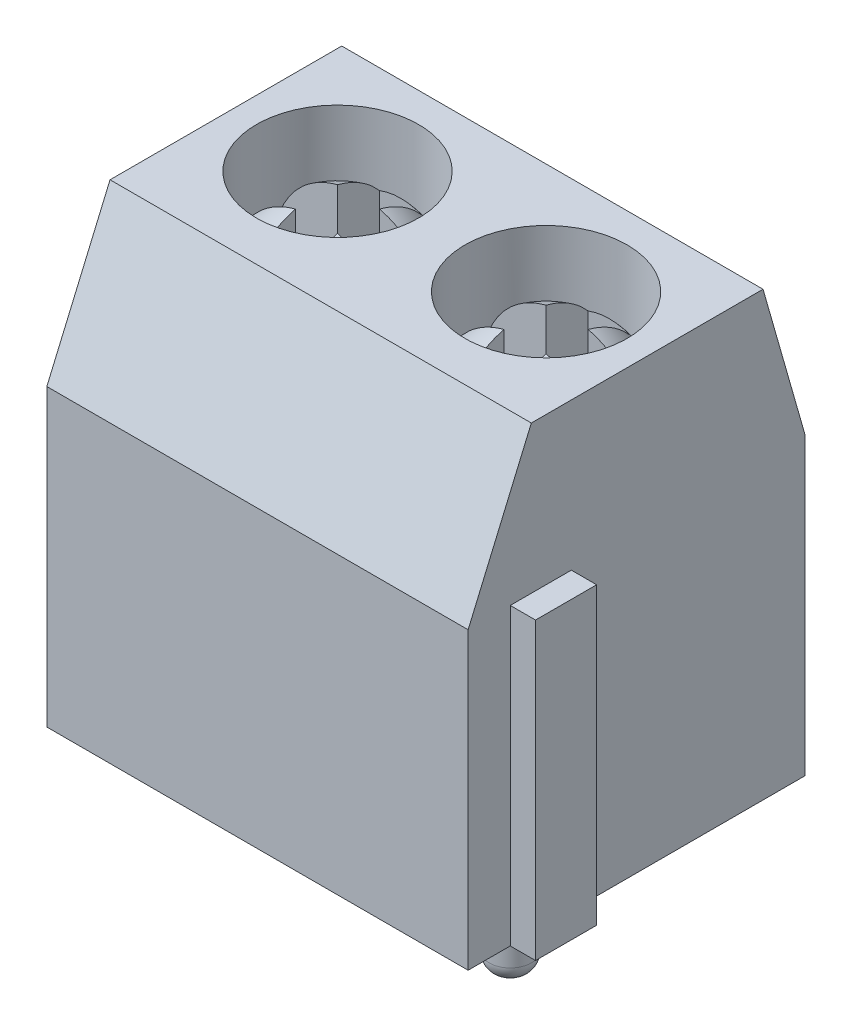
SolidWorks part; units mm, degrees
ref_plane "Plano frontal" through (0, 0, 0) normal (0, 0, 1) x (1, 0, 0)
ref_plane "Plano superior" through (0, 0, 0) normal (0, 1, 0) x (1, 0, 0)
ref_plane "Plano direito" through (0, 0, 0) normal (1, 0, 0) x (0, 0, -1)
sketch "Body Sketch" plane through (0, 0, 0) normal (1, 0, 0) x (0, 0, -1)
  line L0 (0, 0) -> (0, 7)
  line L1 (1.5, 10.5) -> (7, 10.5)
  line L2 (7, 10.5) -> (8, 7)
  line L3 (0, 7) -> (1.5, 10.5)
  line L4 (8, 7) -> (8, 0)
  line L5 (8, 0) -> (0, 0)
  point P3 (0, 0)
  dimension "D1" = 10.5
  dimension "D2" = 1.5
  dimension "D3" = 8
  dimension "D4" = 7
  dimension "D5" = 1
extrude "Body" add sketch "Body Sketch" along normal blind 10
sketch "Terminal Cut Out Sketch" plane through (0, 0, -8) normal (0, 0, -1) x (-1, 0, 0)
  line L0 (0, 0) -> (0, 7) construction
  line L1 (-9.5, 6) -> (-5.5, 6)
  line L2 (-9.5, 6) -> (-9.5, 1)
  line L3 (-9.5, 1) -> (-5.5, 1)
  line L4 (-5.5, 6) -> (-5.5, 1)
  line L5 (-4.5, 6) -> (-0.5, 6)
  line L6 (-4.5, 6) -> (-4.5, 1)
  line L7 (-4.5, 1) -> (-0.5, 1)
  line L8 (-0.5, 6) -> (-0.5, 1)
  line L9 (-10, 0) -> (-10, 7) construction
  line L10 (-10, 0) -> (0, 0) construction
  line L12 (-10, 7) -> (0, 7) construction
  dimension "D1" = 0.5
  dimension "D2" = 1
  dimension "D3" = 0.5
  dimension "D4" = 1
  dimension "D5" = 1
extrude "Terminal Cut Out" cut sketch "Terminal Cut Out Sketch" against normal blind 2
sketch "Sketch3" plane through (0, 0, -8) normal (0, 0, -1) x (-1, 0, 0)
  line L0 (-9.5, 1) -> (-5.5, 1) construction
  line L1 (-8, 1) -> (-7, 1)
  line L2 (-8, 1) -> (-8, 0)
  line L3 (-8, 0) -> (-7, 0)
  line L4 (-7, 1) -> (-7, 0)
  line L5 (-10, 0) -> (0, 0) construction
  line L6 (-4.5, 1) -> (-0.5, 1) construction
  line L7 (-3, 1) -> (-2, 1)
  line L8 (-3, 1) -> (-3, 0)
  line L9 (-3, 0) -> (-2, 0)
  line L10 (-2, 1) -> (-2, 0)
  line L11 (0, 0) -> (0, 7) construction
  line L12 (-10, 0) -> (-10, 7) construction
  dimension "D1" = 2
  dimension "D2" = 2
  dimension "D3" = 4
extrude "Cut-Extrude2" cut sketch "Sketch3" against normal blind 5
sketch "Sketch4" plane through (0, 0, -6) normal (0, 0, -1) x (-1, 0, 0)
  line L1 (-3, 1) -> (-2, 1) construction
  line L2 (-5.5, 6) -> (-9.5, 6) construction
  line L3 (-0.5, 6) -> (-4.5, 6) construction
  circle A0 centre (-7.5, 3.5) radius 1.5
  circle A1 centre (-2.5, 3.5) radius 1.5
  point P8 (-7.5, 6)
  point P11 (-2.5, 6)
  dimension "D1" = 3
  dimension "D2" = 1
extrude "Cut-Extrude3" cut sketch "Sketch4" against normal blind 5
sketch "Sketch6" plane through (0, 0, -6) normal (0, 0, -1) x (-1, 0, 0)
  line L0 (-9.5, 6) -> (-8.5, 3)
  line L1 (-8.5, 3) -> (-6.5, 3)
  line L2 (-6.5, 3) -> (-5.5, 6)
  line L3 (-5.5, 6) -> (-9.5, 6)
  line L4 (-5.5, 6) -> (-4.5, 6) construction
  line L5 (-5, 6) -> (-5, 0.9151) construction
  line L6 (-4.5, 6) -> (-0.5, 6)
  line L7 (-3.5, 3) -> (-4.5, 6)
  line L8 (-1.5, 3) -> (-3.5, 3)
  line L9 (-0.5, 6) -> (-1.5, 3)
  dimension "D1" = 3
  dimension "D2" = 2
extrude "Boss-Extrude2" add sketch "Sketch6" along normal blind 0.1
sketch "Pins Sketch" plane through (0, 1, 0) normal (0, -1, 0) x (1, 0, 0)
  line L6 (2, -3) -> (2, -8) construction
  line L8 (3, -3) -> (3, -8) construction
  line L10 (2, -3) -> (3, -3) construction
  line L13 (8, -3) -> (7, -3) construction
  line L16 (8, -3) -> (8, -8) construction
  line L18 (7, -3) -> (7, -6) construction
  circle A0 centre (2.5, -3.5) radius 0.499
  circle A1 centre (7.5, -3.5) radius 0.499
  dimension "D1" = 0.001
  dimension "D2" = 0.001
  dimension "D3" = 0.001
  dimension "D4" = 0.001
  dimension "D5" = 0.001
  dimension "D6" = 0.001
extrude "Pins" add sketch "Pins Sketch" along normal blind 4
fillet "Pin Ends Fillets" radius 0.4 2 edges at (7.5, -3, -3.999) (2.5, -3, -3.999)
sketch "Link Cut Sketch" plane through (0, 0, 0) normal (-1, 0, 0) x (0, 0, 1)
  line L0 (0, 0) -> (-8, 0) construction
  line L1 (-2.3, 0) -> (-1, 0)
  line L2 (-2.3, 0) -> (-2.3, 7)
  line L3 (-2.3, 7) -> (-1, 7)
  line L4 (-1, 0) -> (-1, 7)
  line L5 (0, 7) -> (0, 0) construction
  dimension "D1" = 1.3
  dimension "D2" = 7
  dimension "D3" = 1
extrude "Link Cut Extrude" cut sketch "Link Cut Sketch" against normal blind 0.6
sketch "Link Boss Sketch" plane through (10, 0, 0) normal (1, 0, 0) x (0, 0, -1)
  line L0 (0, 0) -> (8, 0) construction
  line L1 (1, 0) -> (2.45, 0)
  line L2 (1, 0) -> (1, 7)
  line L3 (1, 7) -> (2.45, 7)
  line L4 (2.45, 0) -> (2.45, 7)
  line L5 (0, 7) -> (0, 0) construction
  dimension "D1" = 1
  dimension "D2" = 1.45
  dimension "D3" = 7
extrude "Link Boss Extrude" add sketch "Link Boss Sketch" along normal blind 0.6
sketch "Screw Hole Sketch" plane through (0, 10.5, 0) normal (0, 1, 0) x (1, 0, 0)
  line L3 (0, 7) -> (0, 1.5) construction
  line L6 (10, 0) -> (0, 0) construction
  line L8 (10, 7) -> (0, 7) construction
  line L9 (5, 7) -> (5, 0) construction
  circle A0 centre (2.525, 4.375) radius 1.925
  circle A3 centre (7.475, 4.375) radius 1.925
  dimension "D1" = 3.85
  dimension "D4" = 0.6
  dimension "D8" = 0.7
extrude "Screw Hole Cut" cut sketch "Screw Hole Sketch" against normal blind 2
sketch "Sketch11" plane through (0, 0, -6.1) normal (0, 0, -1) x (-1, 0, 0)
  line L0 (-4.5, 6) -> (-5.5, 6) construction
  line L1 (-8.5, 3) -> (-6.5, 3)
  line L2 (-8.5, 3) -> (-8.5, 2.9)
  line L3 (-8.5, 2.9) -> (-6.5, 2.9)
  line L4 (-6.5, 3) -> (-6.5, 2.9)
  line L5 (-5, 6) -> (-5, 2.7412) construction
  line L6 (-3.5, 3) -> (-3.5, 2.9)
  line L7 (-1.5, 2.9) -> (-3.5, 2.9)
  line L8 (-1.5, 3) -> (-1.5, 2.9)
  line L9 (-1.5, 3) -> (-3.5, 3)
  dimension "D1" = 0.1
extrude "Boss-Extrude7" add sketch "Sketch11" against normal blind 3
fillet "Fillet1" radius 0.1 2 edges at (2.5, 2.9, -6.1) (7.5, 2.9, -6.1)
sketch "Sketch12" plane through (0, 8.5, 0) normal (0, 1, 0) x (1, 0, 0)
  line L0 (5.55, 4.375) -> (9.4, 4.375)
  circle A0 centre (7.475, 4.375) radius 1.925 construction
  circle A1 centre (7.475, 4.375) radius 1.925 construction
ref_plane "Plane1" through (0, 0, -4.375) normal (0, 0, 1) x (1, 0, 0)
sketch "Sketch13" plane through (0, 0, -4.375) normal (0, 0, 1) x (1, 0, 0)
  line L0 (7.475, 8.5) -> (7.475, 11.5349) construction
  line L1 (5.55, 8.5) -> (9.4, 8.5) construction
  line L2 (7.475, 9.8483) -> (7.475, 8.5)
  line L3 (7.475, 8.5) -> (9.4, 8.5)
  arc A0 (7.475, 9.8483) -> (9.4, 8.5) centre (7.475, 7.8) cw
revolve "Revolve1" add sketch "Sketch13" angle 360 about L0
ref_plane "Plane2" through (5, 0, 0) normal (1, 0, 0) x (0, 0, -1)
sketch "Sketch15" plane through (0, 10.5, 0) normal (0, 1, 0) x (1, 0, 0)
  line L0 (7.475, 6.3) -> (7.475, 2.45) construction
  line L1 (6.975, 5.875) -> (7.975, 5.875)
  line L2 (6.975, 5.875) -> (6.975, 2.875)
  line L3 (6.975, 2.875) -> (7.975, 2.875)
  line L4 (7.975, 5.875) -> (7.975, 2.875)
  line L5 (5.6161, 4.875) -> (9.3339, 4.875)
  line L7 (5.6161, 3.875) -> (9.3339, 3.875)
  line L10 (9.4, 4.375) -> (5.55, 4.375) construction
  arc A0 (5.6161, 4.875) -> (5.6161, 3.875) centre (7.475, 4.375) ccw
  circle A1 centre (7.475, 4.375) radius 1.925 construction
  circle A2 centre (7.475, 4.375) radius 1.925 construction
  arc A3 (9.3339, 3.875) -> (9.3339, 4.875) centre (7.475, 4.375) ccw
  point P4 (7.975, 4.375)
  point P5 (7.475, 5.875)
  circle M1 centre (7.475, 4.375) radius 1.925
  dimension "D1" = 1
  dimension "D2" = 1
  dimension "D3" = 3
  dimension "D4" = 0.5
extrude "Cut-Extrude6" cut sketch "Sketch15" against normal blind 3 contours L4 L7 L5 M1 | L2 L7 L4 L5 | L2 L5 L4 L1 | L7 L2 L5 M1 | L7 L2 L3 L4
mirror "Mirror1" about plane through (5, 0, 0) normal (1, 0, 0) of "Cut-Extrude6", "Revolve1"
sketch "Sketch17" plane through (0, 7.5, 0) normal (0, 1, 0) x (1, 0, 0)
  line L10 (2.025, 4.875) -> (0.6661, 4.875)
  line L11 (0.6661, 3.875) -> (2.025, 3.875)
  line L12 (2.025, 3.875) -> (2.025, 2.875)
  line L13 (2.025, 2.875) -> (3.025, 2.875)
  line L14 (3.025, 2.875) -> (3.025, 3.875)
  line L15 (3.025, 3.875) -> (4.3839, 3.875)
  line L16 (4.3839, 4.875) -> (3.025, 4.875)
  line L17 (3.025, 4.875) -> (3.025, 5.875)
  line L18 (3.025, 5.875) -> (2.025, 5.875)
  line L19 (2.025, 5.875) -> (2.025, 4.875)
  line L20 (2.025, 4.875) -> (0.6661, 4.875)
  line L21 (0.6661, 3.875) -> (2.025, 3.875)
  line L22 (2.025, 3.875) -> (2.025, 2.875)
  line L23 (2.025, 2.875) -> (3.025, 2.875)
  line L24 (3.025, 2.875) -> (3.025, 3.875)
  line L25 (3.025, 3.875) -> (4.3839, 3.875)
  line L26 (4.3839, 4.875) -> (3.025, 4.875)
  line L27 (3.025, 4.875) -> (3.025, 5.875)
  line L28 (3.025, 5.875) -> (2.025, 5.875)
  line L29 (2.025, 5.875) -> (2.025, 4.875)
  line L30 (9.3339, 4.875) -> (7.975, 4.875)
  line L31 (7.975, 4.875) -> (7.975, 5.875)
  line L32 (7.975, 5.875) -> (6.975, 5.875)
  line L33 (6.975, 5.875) -> (6.975, 4.875)
  line L34 (6.975, 4.875) -> (5.6161, 4.875)
  line L35 (5.6161, 3.875) -> (6.975, 3.875)
  line L36 (6.975, 3.875) -> (6.975, 2.875)
  line L37 (6.975, 2.875) -> (7.975, 2.875)
  line L38 (7.975, 2.875) -> (7.975, 3.875)
  line L39 (7.975, 3.875) -> (9.3339, 3.875)
  line L40 (9.3339, 4.875) -> (7.975, 4.875)
  line L41 (7.975, 4.875) -> (7.975, 5.875)
  line L42 (7.975, 5.875) -> (6.975, 5.875)
  line L43 (6.975, 5.875) -> (6.975, 4.875)
  line L44 (6.975, 4.875) -> (5.6161, 4.875)
  line L45 (5.6161, 3.875) -> (6.975, 3.875)
  line L46 (6.975, 3.875) -> (6.975, 2.875)
  line L47 (6.975, 2.875) -> (7.975, 2.875)
  line L48 (7.975, 2.875) -> (7.975, 3.875)
  line L49 (7.975, 3.875) -> (9.3339, 3.875)
  arc A2 (0.6661, 4.875) -> (0.6661, 3.875) centre (2.525, 4.375) ccw
  arc A3 (4.3839, 3.875) -> (4.3839, 4.875) centre (2.525, 4.375) ccw
  arc A4 (0.6661, 4.875) -> (0.6661, 3.875) centre (2.525, 4.375) ccw
  arc A5 (4.3839, 3.875) -> (4.3839, 4.875) centre (2.525, 4.375) ccw
  arc A6 (5.6161, 4.875) -> (5.6161, 3.875) centre (7.475, 4.375) ccw
  arc A7 (9.3339, 3.875) -> (9.3339, 4.875) centre (7.475, 4.375) ccw
  arc A8 (5.6161, 4.875) -> (5.6161, 3.875) centre (7.475, 4.375) ccw
  arc A9 (9.3339, 3.875) -> (9.3339, 4.875) centre (7.475, 4.375) ccw
  dimension "D1" = 0
  dimension "D2" = 0
extrude "Cut-Extrude8" cut sketch "Sketch17" against normal blind 1 draft 20
